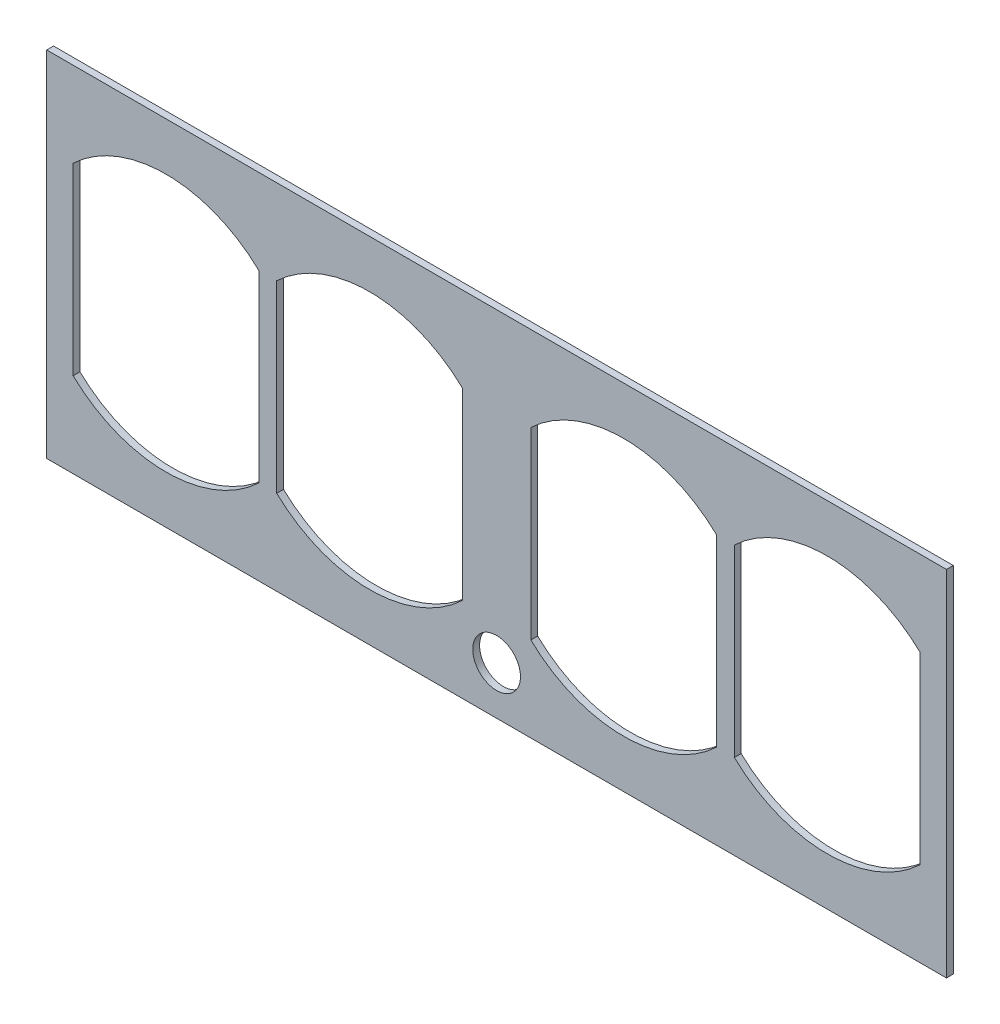
SolidWorks part; units mm, degrees
ref_plane "Спереди" through (0, 0, 0) normal (0, 0, 1) x (1, 0, 0)
ref_plane "Сверху" through (0, 0, 0) normal (0, 1, 0) x (1, 0, 0)
ref_plane "Справа" through (0, 0, 0) normal (1, 0, 0) x (0, 0, -1)
sketch "Эскиз1" plane through (0, 0, 0) normal (0, 0, 1) x (1, 0, 0)
  line L0 (0.0834, -0.0277) -> (-52.9166, -0.0277) construction
  line L1 (-49.6359, 10.7773) -> (-49.6359, -10.8327)
  line L11 (-52.7368, 20.7454) -> (52.9037, 20.7454)
  line L12 (-27.8359, 10.7773) -> (-27.8359, -10.8327)
  line L13 (-38.7359, 15.1223) -> (-38.7359, -15.1777) construction
  line L14 (-25.7359, 10.7773) -> (-25.7359, -10.8327)
  line L15 (-2.8359, -10.8327) -> (0.0834, -0.0277) construction
  line L16 (0.0834, -0.0277) -> (0.0834, -27.2777) construction
  line L17 (-3.9359, 10.7773) -> (-3.9359, -10.8327)
  line L18 (4.1028, 10.7773) -> (4.1028, -10.8327)
  line L19 (25.9028, 10.7773) -> (25.9028, -10.8327)
  line L20 (28.0028, 10.7773) -> (28.0028, -10.8327)
  line L21 (49.8028, 10.7773) -> (49.8028, -10.8327)
  line L22 (-52.7368, 20.7454) -> (-52.7368, -20.8009)
  line L23 (-52.7368, -20.8009) -> (52.9037, -20.8009)
  line L24 (52.9037, 20.7454) -> (52.9037, -20.8009)
  line L25 (-52.7368, 20.7454) -> (52.9037, -20.8009) construction
  line L26 (-52.7368, -20.8009) -> (52.9037, 20.7454) construction
  circle A0 centre (0.0834, -15.1777) radius 2.8
  arc A1 (-49.6359, 10.7773) -> (-27.8359, 10.7773) centre (-38.7359, -0.7223) cw
  arc A2 (-49.6359, -10.8327) -> (-27.8359, -10.8327) centre (-38.7359, 0.6668) ccw
  arc A3 (-25.7359, -10.8327) -> (-3.9359, -10.8327) centre (-14.8359, 0.6668) ccw
  arc A4 (-25.7359, 10.7773) -> (-3.9359, 10.7773) centre (-14.8359, -0.7223) cw
  arc A5 (25.9028, 10.7773) -> (4.1028, 10.7773) centre (15.0028, -0.7223) ccw
  arc A6 (25.9028, -10.8327) -> (4.1028, -10.8327) centre (15.0028, 0.6668) cw
  arc A7 (49.8028, 10.7773) -> (28.0028, 10.7773) centre (38.9028, -0.7223) ccw
  arc A8 (49.8028, -10.8327) -> (28.0028, -10.8327) centre (38.9028, 0.6668) cw
  point P3 (-38.7359, -0.0277)
  point P9 (-38.7359, -0.0277)
  point P14 (-0.7931, 0.3966)
  point P15 (-13.7359, -0.0277)
  point P24 (-13.7359, -0.0277)
  point P41 (13.9028, -0.0277)
  point P42 (38.9028, -0.0277)
  dimension "D1" = 5.6
extrude "Бобышка-Вытянуть2" add sketch "Эскиз1" along normal blind 0.8
